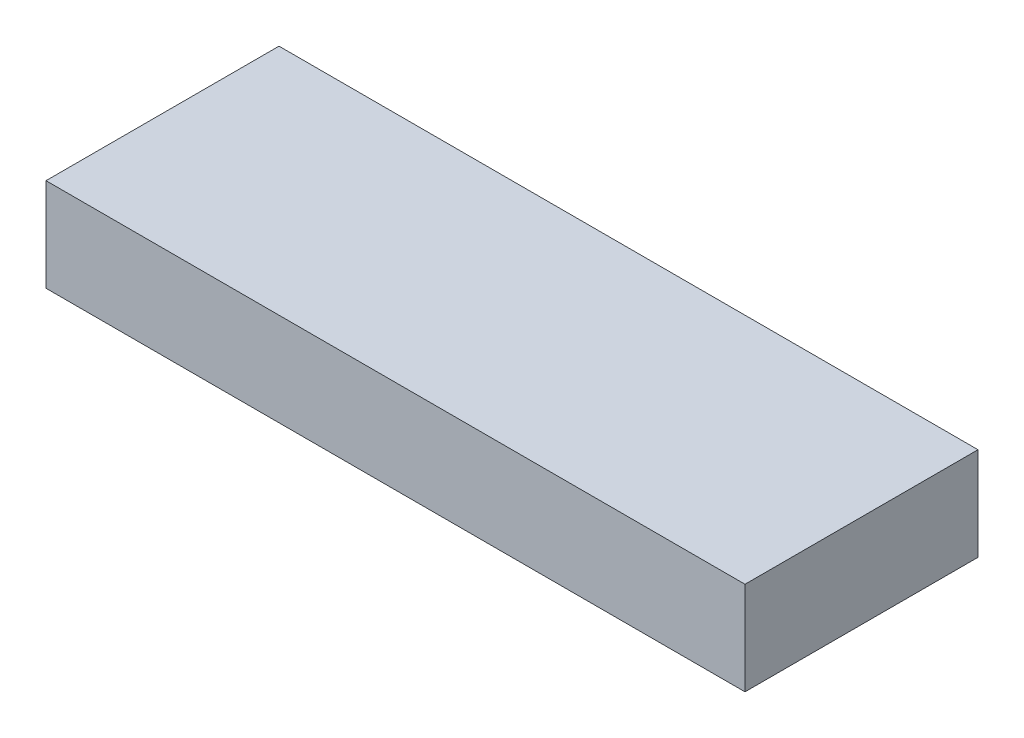
SolidWorks part; units mm, degrees
ref_plane "Front Plane" through (0, 0, 0) normal (0, 0, 1) x (1, 0, 0)
ref_plane "Top Plane" through (0, 0, 0) normal (0, 1, 0) x (1, 0, 0)
ref_plane "Right Plane" through (0, 0, 0) normal (1, 0, 0) x (0, 0, -1)
sketch "Sketch1" plane through (0, 0, 0) normal (0, 0, 1) x (1, 0, 0)
  line L0 (0, 25) -> (0, -25) construction
  line L1 (0, -25) -> (30, -25) construction
  line L2 (30, -25) -> (30, -10) construction
  line L3 (30, -10) -> (180, -10)
  line L4 (180, -10) -> (180, 10)
  line L5 (180, 10) -> (30, 10)
  line L6 (30, 10) -> (30, 25) construction
  line L7 (30, 25) -> (0, 25) construction
  line L8 (30, 10) -> (30, -10)
  point P3 (0, 0)
  point P10 (180, 0)
  dimension "D1" = 30
  dimension "D2" = 20
  dimension "D3" = 150
  dimension "D4" = 50
extrude "Boss-Extrude1" add sketch "Sketch1" along normal blind 50
